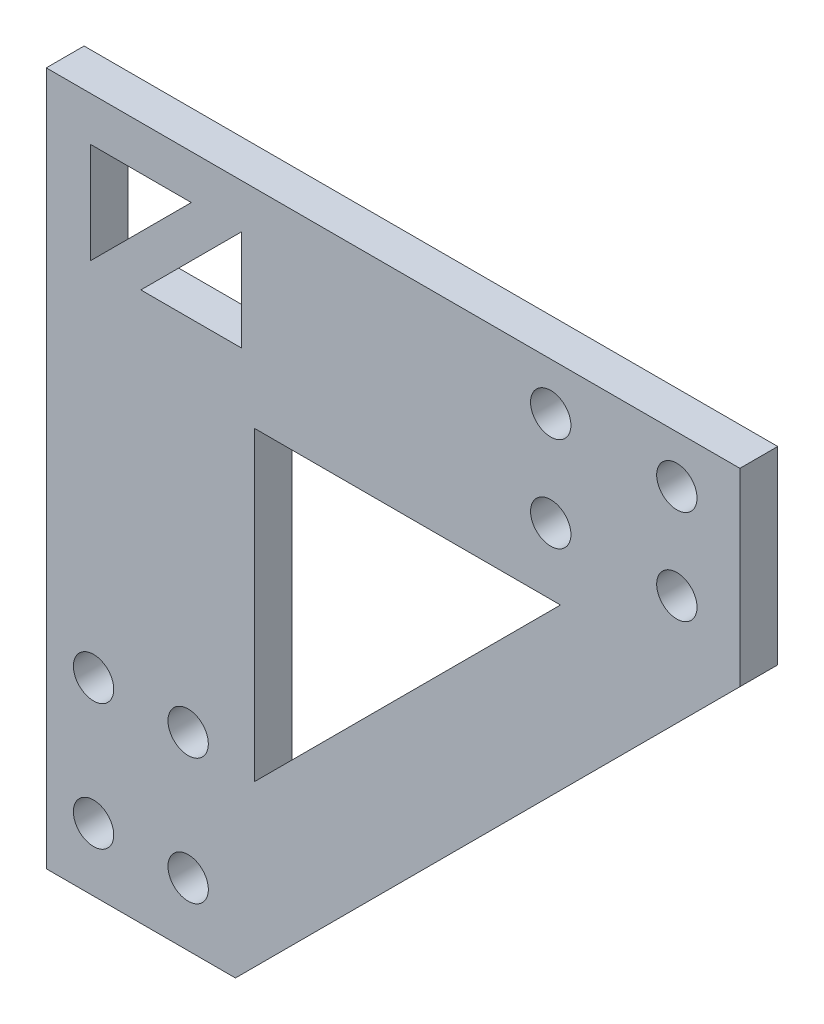
SolidWorks part; units mm, degrees
ref_plane "前视基准面" through (0, 0, 0) normal (0, 0, 1) x (1, 0, 0)
ref_plane "上视基准面" through (0, 0, 0) normal (0, 1, 0) x (1, 0, 0)
ref_plane "右视基准面" through (0, 0, 0) normal (1, 0, 0) x (0, 0, -1)
other "Configuration Table"
sketch "草图1" plane through (0, 0, 0) normal (0, 0, 1) x (1, 0, 0)
  line L0 (0, 0) -> (55, 0)
  line L1 (55, 0) -> (55, -15)
  line L2 (55, -15) -> (15, -55)
  line L3 (15, -55) -> (0, -55)
  line L4 (0, -55) -> (0, 0)
  line L5 (0, -45) -> (25, -45) construction
  line L6 (45, 0) -> (45, -25) construction
  line L7 (7.5, 0) -> (7.5, -55) construction
  line L8 (55, -7.5) -> (0, -7.5) construction
  line L9 (16.5, -16.5) -> (16.5, -40.7721)
  line L10 (16.5, -40.7721) -> (40.7721, -16.5)
  line L11 (40.7721, -16.5) -> (16.5, -16.5)
  line L12 (3.5, -3.5) -> (11.5, -3.5)
  line L13 (11.5, -3.5) -> (3.5, -11.5)
  line L14 (3.5, -3.5) -> (3.5, -11.5)
  line L15 (15.5, -3.5) -> (7.5, -11.5)
  line L16 (7.5, -11.5) -> (15.5, -11.5)
  line L17 (15.5, -11.5) -> (15.5, -3.5)
  circle A0 centre (3.75, -50) radius 1.6
  circle A1 centre (11.25, -50) radius 1.6
  circle A2 centre (11.25, -40) radius 1.6
  circle A3 centre (3.75, -40) radius 1.6
  circle A4 centre (50, -3.75) radius 1.6
  circle A5 centre (50, -11.25) radius 1.6
  circle A6 centre (40, -11.25) radius 1.6
  circle A7 centre (40, -3.75) radius 1.6
  point P34 (28.636, -28.636)
  dimension "D7" = 3.2
  dimension "D10" = 3.2
  dimension "D1" = 15
  dimension "D2" = 15
  dimension "D3" = 45
  dimension "D4" = 45
  dimension "D5" = 10
  dimension "D6" = 10
  dimension "D8" = 3.75
  dimension "D9" = 5
  dimension "D11" = 3.75
  dimension "D12" = 5
  dimension "D13" = 9
  dimension "D14" = 9
  dimension "D15" = 9
  dimension "D16" = 8
  dimension "D17" = 8
  dimension "D18" = 8
  dimension "D19" = 8
extrude "凸台-拉伸1" add sketch "草图1" along normal blind 3
